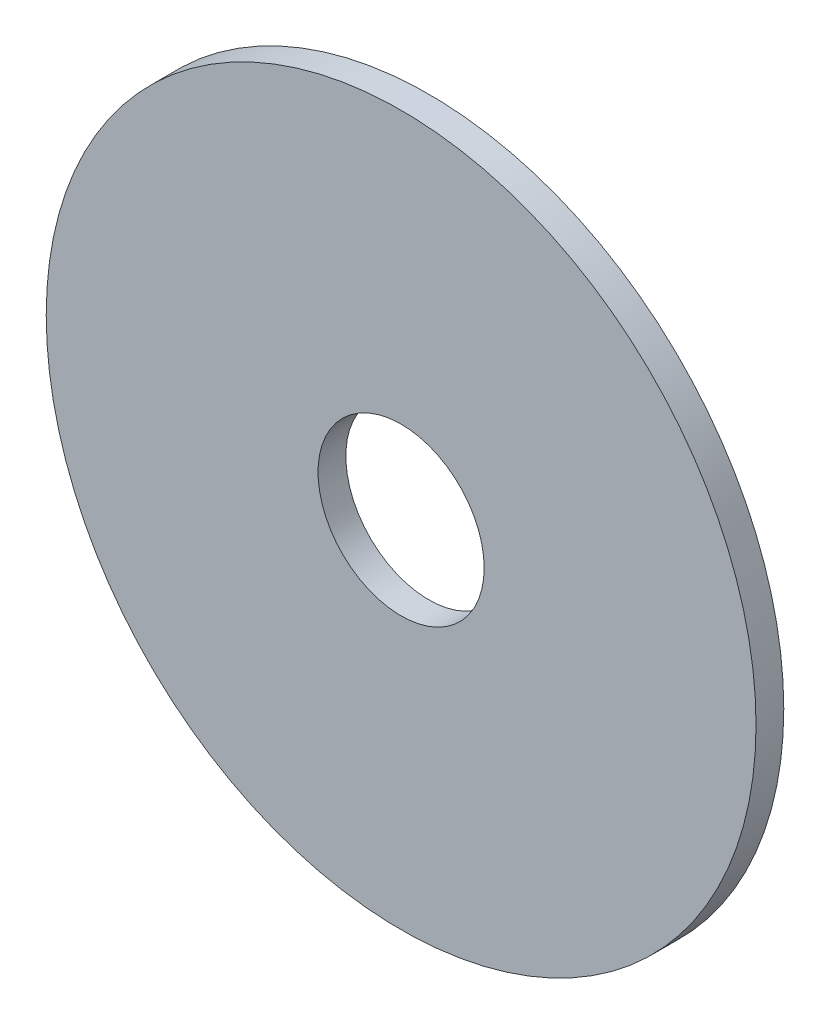
SolidWorks part; units mm, degrees
material "Rubber"
ref_plane "Front Plane" through (0, 0, 0) normal (0, 0, 1) x (1, 0, 0)
ref_plane "Top Plane" through (0, 0, 0) normal (0, 1, 0) x (1, 0, 0)
ref_plane "Right Plane" through (0, 0, 0) normal (1, 0, 0) x (0, 0, -1)
sketch "Sketch1" plane through (0, 0, 0) normal (0, 0, 1) x (1, 0, 0)
  circle A0 centre (0, 0) radius 76.73
extrude "Boss-Extrude1" add sketch "Sketch1" along normal blind 6
sketch "Sketch2" plane through (0, 0, 6) normal (0, 0, 1) x (1, 0, 0)
  circle A0 centre (0, 0) radius 17.9565
extrude "Cut-Extrude1" cut sketch "Sketch2" against normal blind 6
